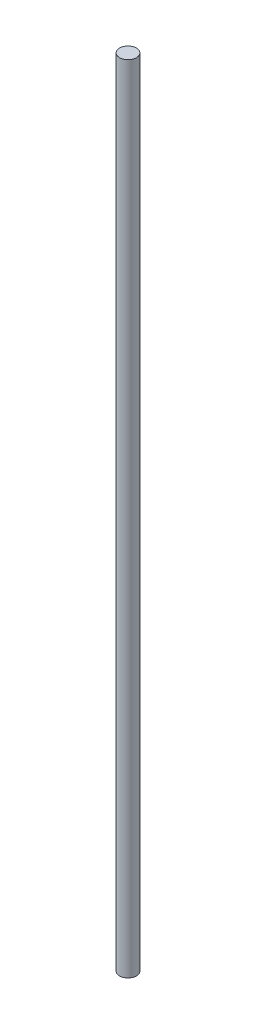
SolidWorks part; units mm, degrees
ref_plane "Front Plane" through (0, 0, 0) normal (0, 0, 1) x (1, 0, 0)
ref_plane "Top Plane" through (0, 0, 0) normal (0, 1, 0) x (1, 0, 0)
ref_plane "Right Plane" through (0, 0, 0) normal (1, 0, 0) x (0, 0, -1)
sketch "Sketch1" plane through (0, 0, 0) normal (0, 1, 0) x (1, 0, 0)
  circle A0 centre (0, 0) radius 4
  dimension "D1" = 8
extrude "Boss-Extrude1" add sketch "Sketch1" along normal blind 379.1
equation "\"d\"= 8"
equation "\"l\"= 372.6 + 6.5"
equation "\"D1@Boss-Extrude1\"=\"l\""
equation "\"D1@Sketch1\"=\"d\""
